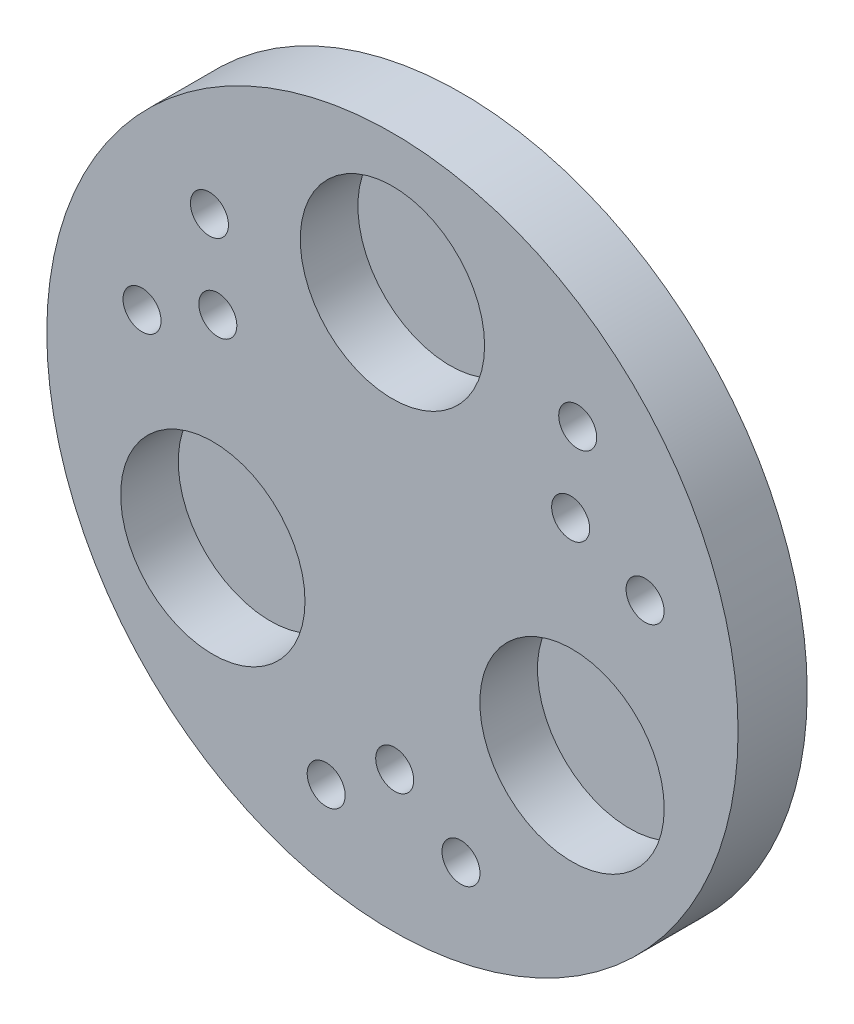
SolidWorks part; units mm, degrees
ref_plane "Front Plane" through (0, 0, 0) normal (0, 0, 1) x (1, 0, 0)
ref_plane "Top Plane" through (0, 0, 0) normal (0, 1, 0) x (1, 0, 0)
ref_plane "Right Plane" through (0, 0, 0) normal (1, 0, 0) x (0, 0, -1)
sketch "Sketch1" plane through (0, 0, 0) normal (0, 0, 1) x (1, 0, 0)
  line L0 (-1000, 0) -> (49000, 0) construction
  line L1 (0, -1000) -> (0, 49000) construction
  circle A0 centre (0, 0) radius 30
  circle A1 centre (0, 0) radius 18 construction
  circle A2 centre (0, 18) radius 8
  circle A5 centre (15.5885, -9) radius 8
  circle A7 centre (-15.5885, -9) radius 8
  point P19 (0, 0)
  dimension "D1" = 60
  dimension "D2" = 36
  dimension "D3" = 16
  dimension "D5" = 3
extrude "Boss-Extrude1" add sketch "Sketch1" along normal mid plane 5 contours A0
sketch "Sketch3" plane through (0, 0, -2.5) normal (0, 0, -1) x (-1, 0, 0)
  circle A0 centre (0, 0) radius 30 construction
  circle A1 centre (0, 0) radius 30
extrude "Boss-Extrude2" add sketch "Sketch3" along normal blind 1
sketch "Sketch4" plane through (0, 0, -3.5) normal (0, 0, -1) x (-1, 0, 0)
  line L0 (0, 0) -> (22.5, 0) construction
  line L1 (0, 0) -> (21.7333, 5.8234) construction
  line L2 (0, 0) -> (15.1554, 8.75) construction
  circle A3 centre (0, 0) radius 22.5 construction
  circle A4 centre (0, 0) radius 30
  circle A5 centre (0, 0) radius 30 construction
  circle A6 centre (0, 0) radius 17.5 construction
  dimension "D1" = 0
  dimension "D2" = 45
  dimension "D3" = 35
  dimension "D4" = 30
  dimension "D5" = 15
hole_wizard "M4x0.7 Tapped Hole1" positions "Sketch5" profile "Sketch6" tap size "M4x0.7" standard "ANSI Metric"
sketch "Sketch5" plane through (0, 0, -3.5) normal (0, 0, -1) x (-1, 0, 0)
  point P0 (21.7333, 5.8234)
sketch "Sketch6" plane through (-21.7333, 5.8234, -3.5) normal (1, 0, 0) x (0, 1, 0)
  line L0 (0, 0) -> (0, 11.0914)
  line L1 (0, 11.0914) -> (1.65, 10.1)
  line L2 (1.65, 10.1) -> (1.65, 0.375)
  line L3 (1.65, 0.375) -> (2.025, 0)
  line L5 (2.025, 0) -> (0, 0)
  line L6 (-1.65, 0.375) -> (-2.025, 0) construction
  line L10 (0, 11.0914) -> (-1.65, 10.1) construction
  line L11 (0, -6.35) -> (0, 107.95) construction
  dimension "Tap Drill Dia." = 3.3
  dimension "Tap Drill Depth" = 10.1
  dimension "Near C'Sink Dia." = 4.05
  dimension "Near C'Sink Angle" = 90
  dimension "Drill Angle" = 118
cosmetic thread "Hole Thread25" parameters "D1"=8, "D2"=4
hole_wizard "M4x0.7 Tapped Hole2" positions "Sketch7" profile "Sketch8" tap size "M4x0.7" standard "ANSI Metric"
sketch "Sketch7" plane through (0, 0, -3.5) normal (0, 0, -1) x (-1, 0, 0)
  point P0 (15.1554, 8.75)
sketch "Sketch8" plane through (-15.1554, 8.75, -3.5) normal (1, 0, 0) x (0, 1, 0)
  line L0 (0, 0) -> (0, 11.0914)
  line L1 (0, 11.0914) -> (1.65, 10.1)
  line L2 (1.65, 10.1) -> (1.65, 0.375)
  line L3 (1.65, 0.375) -> (2.025, 0)
  line L5 (2.025, 0) -> (0, 0)
  line L6 (-1.65, 0.375) -> (-2.025, 0) construction
  line L10 (0, 11.0914) -> (-1.65, 10.1) construction
  line L11 (0, -6.35) -> (0, 107.95) construction
  dimension "Tap Drill Dia." = 3.3
  dimension "Tap Drill Depth" = 10.1
  dimension "Near C'Sink Dia." = 4.05
  dimension "Near C'Sink Angle" = 90
  dimension "Drill Angle" = 118
cosmetic thread "Hole Thread26" parameters "D1"=8, "D2"=4
pattern_circular "CirPattern1" count 3 over 360 about axis through (0.1696, -0.067, 0) along (0, 0, 1) of "M4x0.7 Tapped Hole2"
pattern_circular "CirPattern2" count 12 over 360 about axis through (0.0985, -0.0261, 0) along (0, 0, 1) skipping 2, 3, 6, 7, 10, 11 of "M4x0.7 Tapped Hole1"
